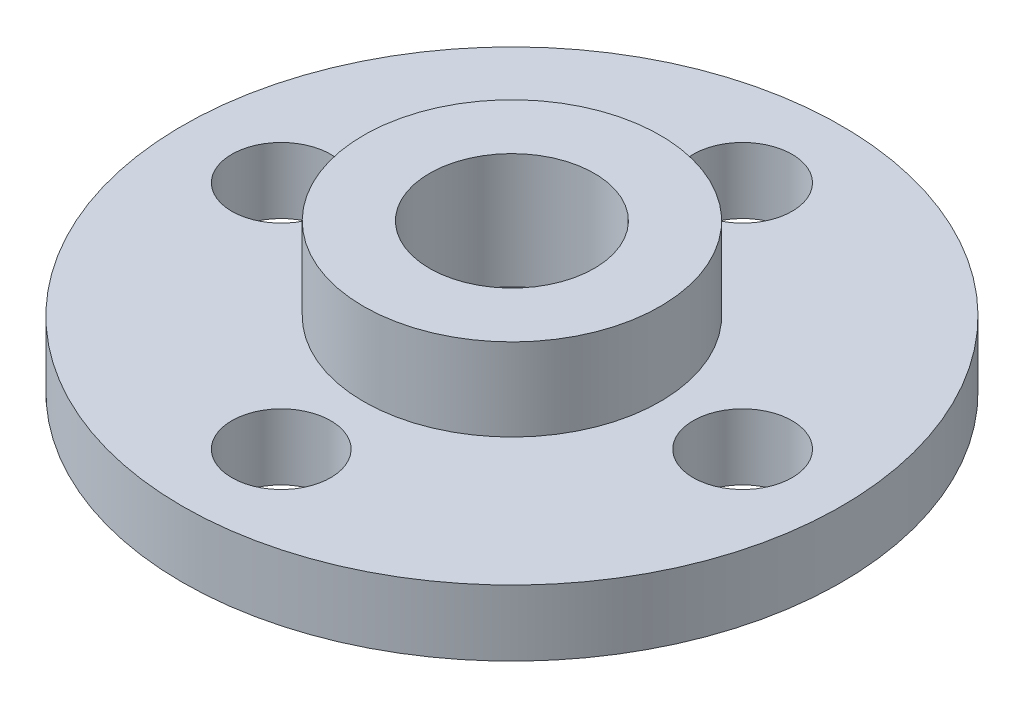
SolidWorks part; units mm, degrees
ref_plane "前视基准面" through (0, 0, 0) normal (0, 0, 1) x (1, 0, 0)
ref_plane "上视基准面" through (0, 0, 0) normal (0, 1, 0) x (1, 0, 0)
ref_plane "右视基准面" through (0, 0, 0) normal (1, 0, 0) x (0, 0, -1)
sketch "草图1" plane through (0, 0, 0) normal (0, 1, 0) x (1, 0, 0)
  circle A0 centre (0, 0) radius 10
  circle A1 centre (0, 7) radius 1.5
  circle A2 centre (7, 0) radius 1.5
  circle A3 centre (0, -7) radius 1.5
  circle A4 centre (-7, 0) radius 1.5
  point P14 (0, 0)
  dimension "D1" = 20
  dimension "D2" = 3
  dimension "D3" = 7
  dimension "D4" = 4
extrude "凸台-拉伸1" add sketch "草图1" along normal blind 2
sketch "草图2" plane through (0, 2, 0) normal (0, 1, 0) x (1, 0, 0)
  circle A0 centre (0, 0) radius 4.5
  dimension "D1" = 9
extrude "凸台-拉伸2" add sketch "草图2" along normal blind 2.5
sketch "草图3" plane through (0, 4.5, 0) normal (0, 1, 0) x (1, 0, 0)
  circle A0 centre (0, 0) radius 1.5
  dimension "D1" = 3
extrude "切除-拉伸1" cut sketch "草图3" against normal through all
sketch "草图4" plane through (0, 4.5, 0) normal (0, 1, 0) x (1, 0, 0)
  circle A0 centre (0, 0) radius 2.5
  dimension "D1" = 5
extrude "切除-拉伸2" cut sketch "草图4" against normal blind 3.5
